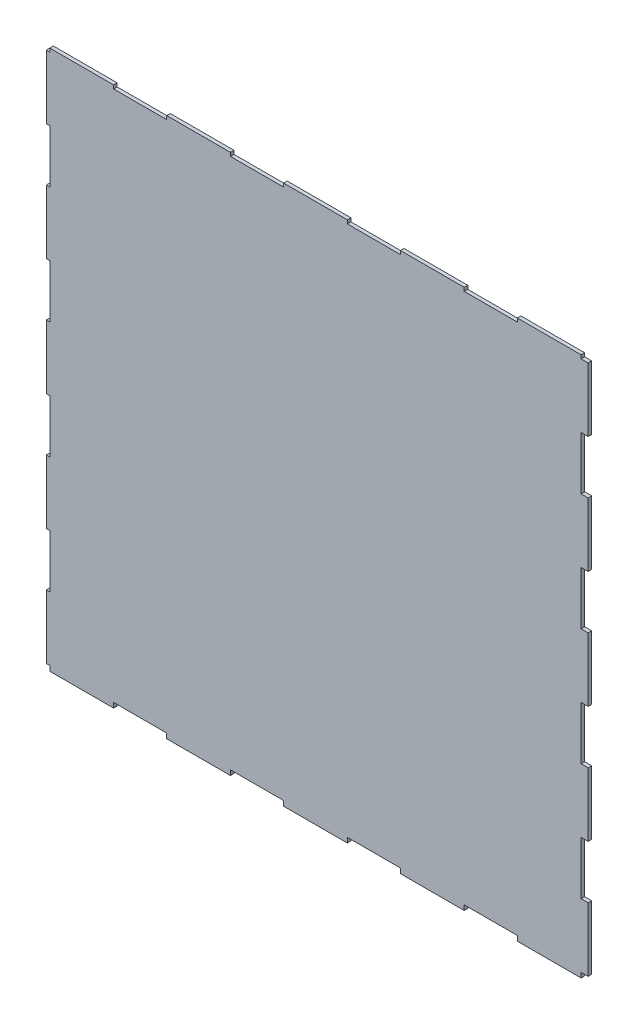
SolidWorks part; units mm, degrees
ref_plane "Front Plane" through (0, 0, 0) normal (0, 0, 1) x (1, 0, 0)
ref_plane "Top Plane" through (0, 0, 0) normal (0, 1, 0) x (1, 0, 0)
ref_plane "Right Plane" through (0, 0, 0) normal (1, 0, 0) x (0, 0, -1)
sketch "Sketch1" plane through (0, 0, 0) normal (0, 0, 1) x (1, 0, 0)
  line L1 (68.9833, -49.7132) -> (-83.4167, -49.7132)
  line L2 (68.9833, -49.7132) -> (68.9833, 102.6868)
  line L3 (68.9833, 102.6868) -> (-83.4167, 102.6868)
  line L4 (-83.4167, -49.7132) -> (-83.4167, 102.6868)
  line L5 (-49.8887, 102.6868) -> (-31.6007, 102.6868)
  line L6 (-49.8887, 102.6868) -> (-49.8887, 103.7028)
  line L7 (-49.8887, 103.7028) -> (-31.6007, 103.7028)
  line L8 (-31.6007, 102.6868) -> (-31.6007, 103.7028)
  line L9 (-16.3607, 102.6868) -> (1.9273, 102.6868)
  line L10 (-16.3607, 102.6868) -> (-16.3607, 103.7028)
  line L11 (-16.3607, 103.7028) -> (1.9273, 103.7028)
  line L12 (1.9273, 102.6868) -> (1.9273, 103.7028)
  line L13 (17.1673, 102.6868) -> (35.4553, 102.6868)
  line L14 (17.1673, 102.6868) -> (17.1673, 103.7028)
  line L15 (17.1673, 103.7028) -> (35.4553, 103.7028)
  line L16 (35.4553, 102.6868) -> (35.4553, 103.7028)
  line L17 (50.6953, 102.6868) -> (68.9833, 102.6868)
  line L18 (50.6953, 102.6868) -> (50.6953, 103.7028)
  line L19 (50.6953, 103.7028) -> (68.9833, 103.7028)
  line L20 (68.9833, 102.6868) -> (68.9833, 103.7028)
  line L25 (-83.4167, 102.6868) -> (-65.1287, 102.6868)
  line L26 (-83.4167, 102.6868) -> (-83.4167, 103.7028)
  line L27 (-83.4167, 103.7028) -> (-65.1287, 103.7028)
  line L28 (-65.1287, 102.6868) -> (-65.1287, 103.7028)
  line L29 (-70.7167, 89.9868) -> (56.2833, 89.9868)
  line L30 (-70.7167, 89.9868) -> (-70.7167, -37.0132)
  line L31 (-70.7167, -37.0132) -> (56.2833, -37.0132)
  line L32 (56.2833, 89.9868) -> (56.2833, -37.0132)
  line L33 (-83.4167, 102.6868) -> (-84.4327, 102.6868)
  line L34 (-83.4167, 102.6868) -> (-83.4167, 84.3988)
  line L35 (-83.4167, 84.3988) -> (-84.4327, 84.3988)
  line L36 (-84.4327, 102.6868) -> (-84.4327, 84.3988)
  line L37 (-83.4167, 69.1588) -> (-84.4327, 69.1588)
  line L38 (-83.4167, 69.1588) -> (-83.4167, 50.8708)
  line L39 (-83.4167, 50.8708) -> (-84.4327, 50.8708)
  line L40 (-84.4327, 69.1588) -> (-84.4327, 50.8708)
  line L41 (-83.4167, 35.6308) -> (-84.4327, 35.6308)
  line L42 (-83.4167, 35.6308) -> (-83.4167, 17.3428)
  line L43 (-83.4167, 17.3428) -> (-84.4327, 17.3428)
  line L44 (-84.4327, 35.6308) -> (-84.4327, 17.3428)
  line L45 (-83.4167, 2.1028) -> (-84.4327, 2.1028)
  line L46 (-83.4167, 2.1028) -> (-83.4167, -16.1852)
  line L47 (-83.4167, -16.1852) -> (-84.4327, -16.1852)
  line L48 (-84.4327, 2.1028) -> (-84.4327, -16.1852)
  line L49 (-83.4167, -49.7132) -> (-84.4327, -49.7132)
  line L50 (-83.4167, -49.7132) -> (-83.4167, -31.4252)
  line L51 (-83.4167, -31.4252) -> (-84.4327, -31.4252)
  line L52 (-84.4327, -49.7132) -> (-84.4327, -31.4252)
  line L53 (-83.4167, -49.7132) -> (-65.1287, -49.7132)
  line L54 (-83.4167, -49.7132) -> (-83.4167, -51.1285)
  line L55 (-83.4167, -51.1285) -> (-65.1287, -51.1285)
  line L56 (-65.1287, -49.7132) -> (-65.1287, -51.1285)
  line L57 (-49.8887, -49.7132) -> (-31.6007, -49.7132)
  line L58 (-49.8887, -49.7132) -> (-49.8887, -51.1285)
  line L59 (-49.8887, -51.1285) -> (-31.6007, -51.1285)
  line L60 (-31.6007, -49.7132) -> (-31.6007, -51.1285)
  line L61 (-16.3607, -49.7132) -> (1.9273, -49.7132)
  line L62 (-16.3607, -49.7132) -> (-16.3607, -51.1285)
  line L63 (-16.3607, -51.1285) -> (1.9273, -51.1285)
  line L64 (1.9273, -49.7132) -> (1.9273, -51.1285)
  line L65 (17.1673, -49.7132) -> (35.4553, -49.7132)
  line L66 (17.1673, -49.7132) -> (17.1673, -51.1285)
  line L67 (17.1673, -51.1285) -> (35.4553, -51.1285)
  line L68 (35.4553, -49.7132) -> (35.4553, -51.1285)
  line L69 (68.9833, -49.7132) -> (50.6953, -49.7132)
  line L70 (68.9833, -49.7132) -> (68.9833, -51.1285)
  line L71 (68.9833, -51.1285) -> (50.6953, -51.1285)
  line L72 (50.6953, -49.7132) -> (50.6953, -51.1285)
  line L73 (68.9833, 102.6868) -> (71.0153, 102.6868)
  line L74 (68.9833, 102.6868) -> (68.9833, 84.3988)
  line L75 (68.9833, 84.3988) -> (71.0153, 84.3988)
  line L76 (71.0153, 102.6868) -> (71.0153, 84.3988)
  line L77 (68.9833, 69.1588) -> (71.0153, 69.1588)
  line L78 (68.9833, 69.1588) -> (68.9833, 50.8708)
  line L79 (68.9833, 50.8708) -> (71.0153, 50.8708)
  line L80 (71.0153, 69.1588) -> (71.0153, 50.8708)
  line L81 (68.9833, 35.6308) -> (71.0153, 35.6308)
  line L82 (68.9833, 35.6308) -> (68.9833, 17.3428)
  line L83 (68.9833, 17.3428) -> (71.0153, 17.3428)
  line L84 (71.0153, 35.6308) -> (71.0153, 17.3428)
  line L85 (68.9833, 2.1028) -> (71.0153, 2.1028)
  line L86 (68.9833, 2.1028) -> (68.9833, -16.1852)
  line L87 (68.9833, -16.1852) -> (71.0153, -16.1852)
  line L88 (71.0153, 2.1028) -> (71.0153, -16.1852)
  line L89 (68.9833, -49.7132) -> (71.0153, -49.7132)
  line L90 (68.9833, -49.7132) -> (68.9833, -31.4252)
  line L91 (68.9833, -31.4252) -> (71.0153, -31.4252)
  line L92 (71.0153, -49.7132) -> (71.0153, -31.4252)
  point P70 (69.9993, 84.3988)
  dimension "D1" = 152.4
  dimension "D2" = 152.4
  dimension "D3" = 1.016
  dimension "D4" = 1.016
  dimension "D5" = 1.016
  dimension "D6" = 1.016
  dimension "D7" = 18.288
  dimension "D8" = 18.288
  dimension "D9" = 18.288
  dimension "D10" = 18.288
  dimension "D11" = 0
  dimension "D12" = 15.24
  dimension "D13" = 15.24
  dimension "D14" = 15.24
  dimension "D15" = 18.288
  dimension "D16" = 12.7
  dimension "D17" = 12.7
  dimension "D18" = 12.7
  dimension "D19" = 12.7
  dimension "D20" = 1.016
  dimension "D21" = 18.288
  dimension "D22" = 18.288
  dimension "D23" = 18.288
  dimension "D24" = 18.288
  dimension "D25" = 18.288
  dimension "D26" = 15.24
  dimension "D27" = 15.24
  dimension "D28" = 15.24
  dimension "D29" = 18.288
  dimension "D30" = 18.288
  dimension "D31" = 15.24
  dimension "D32" = 15.24
  dimension "D33" = 18.288
  dimension "D34" = 18.288
  dimension "D35" = 15.24
  dimension "D36" = 18.288
  dimension "D37" = 18.288
  dimension "D38" = 1.016
  dimension "D39" = 18.288
  dimension "D40" = 0
  dimension "D41" = 15.24
  dimension "D42" = 15.24
  dimension "D43" = 18.288
  dimension "D44" = 15.24
  dimension "D45" = 18.288
  dimension "D46" = 18.288
extrude "Boss-Extrude1" add sketch "Sketch1" along normal blind 1.016 contours L4 L1 L2 L3 L29 L32 L31 L30 | L3 L20 L19 L18 | L76 L73 L2 L75 | L3 L16 L15 L14 | L3 L12 L11 L10 | L3 L8 L7 L6 | L3 L28 L27 L26 | L33 L36 L35 L4 | L37 L40 L39 L4 | L52 L49 L4 L51 | L56 L1 L54 L55 | L60 L1 L58 L59 | L68 L1 L66 L67 | L64 L1 L62 L63 | L1 L72 L71 L70 | L89 L92 L91 L2 | L88 L85 L2 L87 | L84 L81 L2 L83 | L80 L77 L2 L79 | L32 L29 L30 L31 | L44 L43 L42 L41 | L48 L47 L46 L45
